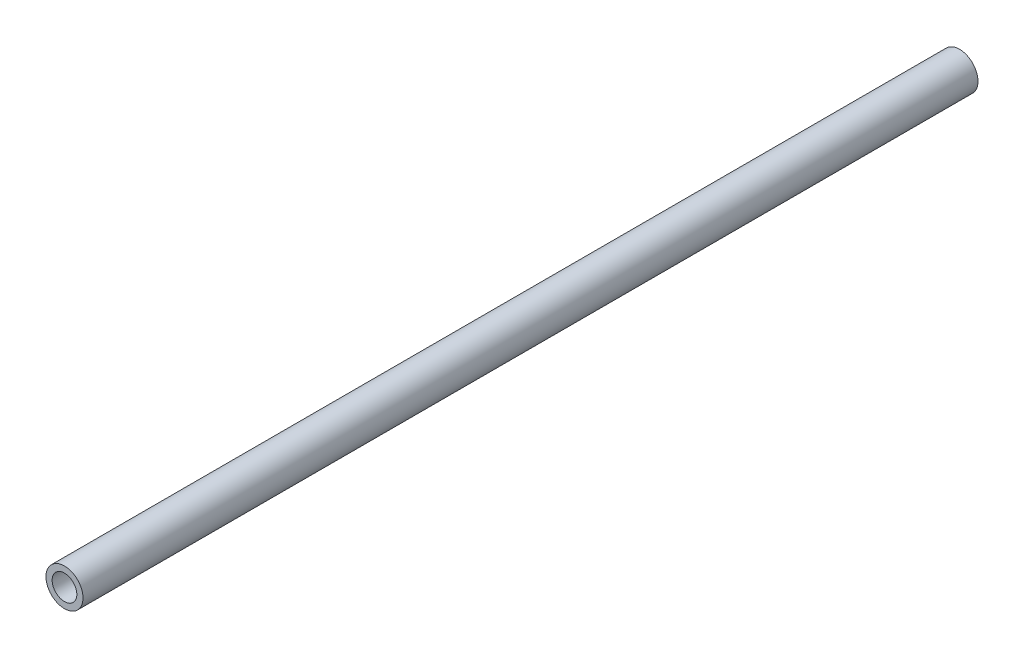
SolidWorks part; units mm, degrees
material "Poltrusion Carbon Fiber"
ref_plane "Front Plane" through (0, 0, 0) normal (0, 0, 1) x (1, 0, 0)
ref_plane "Top Plane" through (0, 0, 0) normal (0, 1, 0) x (1, 0, 0)
ref_plane "Right Plane" through (0, 0, 0) normal (1, 0, 0) x (0, 0, -1)
sketch "Sketch1" plane through (0, 0, 0) normal (0, 0, 1) x (1, 0, 0)
  circle A0 centre (0, 0) radius 3
  circle A1 centre (0, 0) radius 2
  dimension "D1" = 6
  dimension "D2" = 1
extrude "Boss-Extrude1" add sketch "Sketch1" along normal mid plane 145
equation "\"DTailTube\"= 16mm'Диаметр трубки хвостового оперения"
equation "\"FusLenght\"= 700mm"
equation "\"DMotor\"= 35.2mm"
equation "\"MotorArm\"= 320mm"
equation "\"DFus\"= 150mm"
equation "\"DFusTube\"= 30mm'Диаметр трубки внутри фюзеляжа"
equation "\"FusTubeHeight\"= 40mm"
equation "\"FusCentralPartLenght\"= 410mm"
equation "\"FusNoseLenght\"= 150mm"
equation "\"WingOffset\"= 1mm'Расстояние от внутренней поверхности фюзеляжа до профиля крыла по вертикали"
equation "\"EllipseRatio\"= 0.95'Центральная часть фюзеляжа - эллипс. Этот параметр - отношение длин осей эллипса"
equation "\"FrameOffset\"= 0.6mm"
equation "\"DThreadedInsert\"= 3mm'Внешний диамер резьбовых втулок"
equation "\"ThreadedInsertLenght\"=4mm'Длина резьбовых втулок"
equation "\"ThreadedInsertThread\"=2mm'Диаметр резьбы втулки"
equation "\"CenterSectionLenght\"= 140mm'Длина центроплана"
equation "\"b\"= 1700mm'Размах"
equation "\"cwr\"= 236mm'Корневая хорда крыла"
equation "\"TR\"= 0.75'Сужение крыла"
equation "\"cwt\"= \"TR\" * \"cwr\"'Концевая хорда крыла"
equation "\"DWingMainSpar\"= 16mm'Диаметр главного лонжерона крыла"
equation "\"DWingSecondSpar\"= 8mm'Диаметр второго лонжерона крыла"
equation "\"WingSparsDistance\"= 80mm'Расстояния между отверстиями по лонжерон крыла"
equation "\"c\"= 210mm'САХ крыла"
equation "\"FusTubeLenght\"= \"FusLenght\"-90mm'Длина трубки фюзеляжа"
equation "\"bt\"=291mm'Высота лопатки хвоста"
equation "\"ct\"=182mm'Корневая хорда хвоста"
equation "\"lambda_t\"=0.3'Доля хвоста, занатая рулем высоты"
equation "\"TailTubeLenght\"=680mm'Длина хвостовой балки"
equation "\"DStringer\"=6mm'Диаметр стрингеров"
equation "\"TailConnectorBaseLenght\"=20mm'Высота основания конектора хвоста"
equation "\"CargoHolderHoleDistance\"=30mm'Расстояние между крепежными отверстиями для держателя груза"
equation "\"FuselageThickness\"=1.2mm'Толщина фюзеляжа"
equation "\"DTailSpar\"=6mm'Диаметр лонжерона хвостового оперения"
equation "\"TailSparDistance\"=40mm'Расстояние между лонжеронами хвостового оперения"
equation "\"CrossSectionWidth\"=15mm'Ширина кольцевой части шпангоута"
equation "\"HingeLenght\"=30mm'Длина отверстия под шарнир хвостового оперения"
equation "\"HingeWidth\"=2.4mm'Высота отверстия под шарнир ХО"
equation "\"HingeDepth\"=15mm'Глубина отверстия под шарнир ХО"
equation "\"D1@Sketch1\"=\"DTailSpar\""
